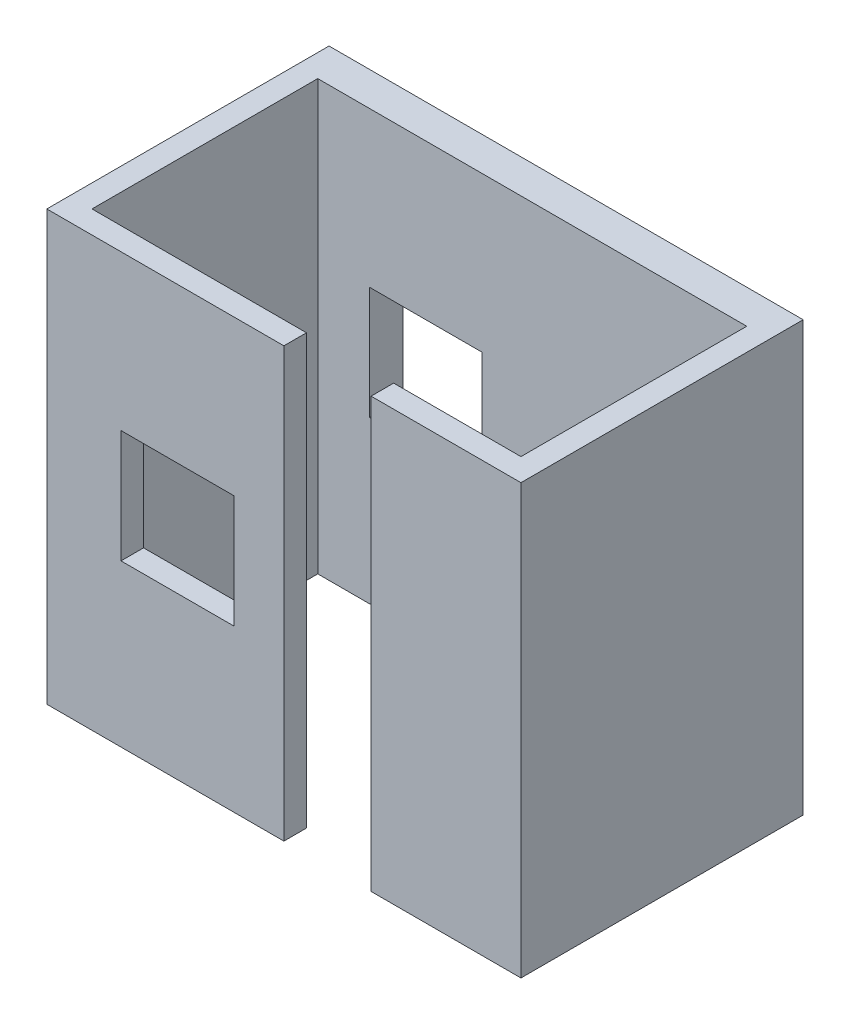
SolidWorks part; units mm, degrees
ref_plane "Front Plane" through (0, 0, 0) normal (0, 0, 1) x (1, 0, 0)
ref_plane "Top Plane" through (0, 0, 0) normal (0, 1, 0) x (1, 0, 0)
ref_plane "Right Plane" through (0, 0, 0) normal (1, 0, 0) x (0, 0, -1)
sketch "Sketch1" plane through (0, 0, 0) normal (0, 0, 1) x (1, 0, 0)
  line L1 (-26.8167, 7.92) -> (-7.8167, 7.92)
  line L2 (-26.8167, 7.92) -> (-26.8167, -11.08)
  line L3 (-26.8167, -11.08) -> (-7.8167, -11.08)
  line L4 (-7.8167, 7.92) -> (-7.8167, -11.08)
  dimension "D1" = 19
  dimension "D2" = 19
extrude "Boss-Extrude1" add sketch "Sketch1" along normal blind 1.5
sketch "Sketch2" plane through (0, 0, 0) normal (0, 0, -1) x (-1, 0, 0)
  line L1 (19.5313, 1.0626) -> (24.5313, 1.0626)
  line L2 (19.5313, 1.0626) -> (19.5313, -3.9374)
  line L3 (19.5313, -3.9374) -> (24.5313, -3.9374)
  line L4 (24.5313, 1.0626) -> (24.5313, -3.9374)
  line L5 (19.5313, 1.0626) -> (24.5313, -3.9374) construction
  line L6 (19.5313, -3.9374) -> (24.5313, 1.0626) construction
  point P0 (22.0313, -1.4374)
  dimension "D1" = 5
  dimension "D2" = 5
extrude "Cut-Extrude1" cut sketch "Sketch2" against normal through all
sketch "Sketch4" plane through (0, 0, 1.5) normal (0, 0, 1) x (1, 0, 0)
  line L1 (-7.8167, 7.92) -> (-6.8167, 7.92)
  line L2 (-7.8167, 7.92) -> (-7.8167, -11.08)
  line L3 (-7.8167, -11.08) -> (-6.8167, -11.08)
  line L4 (-6.8167, 7.92) -> (-6.8167, -11.08)
  line L5 (-26.8167, 7.92) -> (-27.8167, 7.92)
  line L6 (-26.8167, 7.92) -> (-26.8167, -11.08)
  line L7 (-26.8167, -11.08) -> (-27.8167, -11.08)
  line L8 (-27.8167, 7.92) -> (-27.8167, -11.08)
  dimension "D1" = 1
  dimension "D2" = 1
extrude "Boss-Extrude2" add sketch "Sketch4" along normal blind 10 and the other way through all
sketch "Sketch5" plane through (0, 7.92, 0) normal (0, 1, 0) x (-1, 0, 0)
  line L1 (27.8167, 11.5) -> (6.8167, 11.5)
  line L2 (27.8167, 11.5) -> (27.8167, 12.5)
  line L3 (27.8167, 12.5) -> (6.8167, 12.5)
  line L4 (6.8167, 11.5) -> (6.8167, 12.5)
  dimension "D1" = 1
extrude "Boss-Extrude3" add sketch "Sketch5" against normal up to surface (19 mm away) up to face at (-18.5042, -11.08, 4.875)
sketch "Sketch6" plane through (0, 0, 11.5) normal (0, 0, -1) x (-1, 0, 0)
  line L1 (19.5313, 1.0626) -> (24.5313, 1.0626)
  line L2 (19.5313, 1.0626) -> (19.5313, -3.9374)
  line L3 (19.5313, -3.9374) -> (24.5313, -3.9374)
  line L4 (24.5313, 1.0626) -> (24.5313, -3.9374)
extrude "Cut-Extrude2" cut sketch "Sketch6" against normal through all
sketch "Sketch7" plane through (0, 0, 12.5) normal (0, 0, -1) x (-1, 0, 0)
  line L0 (6.8167, 7.92) -> (27.8167, 7.92) construction
  line L1 (13.4542, 7.92) -> (17.3167, 7.92)
  line L2 (13.4542, 7.92) -> (13.4542, -11.08)
  line L3 (13.4542, -11.08) -> (17.3167, -11.08)
  line L4 (17.3167, 7.92) -> (17.3167, -11.08)
  line L5 (27.8167, -11.08) -> (6.8167, -11.08) construction
extrude "Cut-Extrude3" cut sketch "Sketch7" against normal up to surface (11 mm away)
